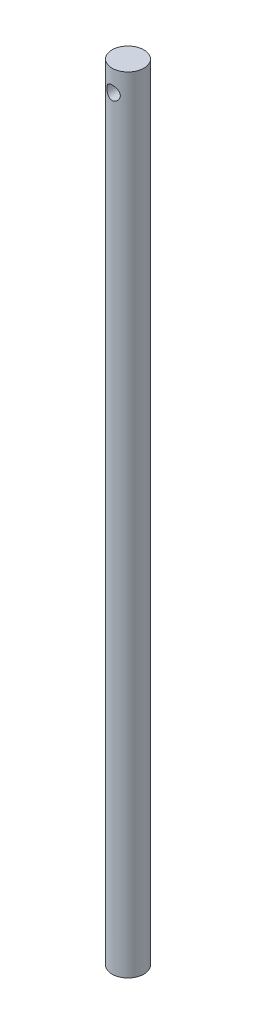
SolidWorks part; units mm, degrees
ref_plane "Frontal Plane" through (0, 0, 0) normal (0, 0, 1) x (1, 0, 0)
ref_plane "Horizontal Plane" through (0, 0, 0) normal (0, 1, 0) x (1, 0, 0)
ref_plane "Profile Plane" through (0, 0, 0) normal (1, 0, 0) x (0, 0, -1)
sketch "Sketch1" plane through (0, 0, 0) normal (0, 1, 0) x (1, 0, 0)
  circle A0 centre (0, 0) radius 7.5
  dimension "D1" = 15
extrude "Boss-Extrude1" add sketch "Sketch1" along normal blind 350
ref_plane "Plane1" through (0, 350, 0) normal (0, 1, 0) x (1, 0, 0)
sketch "Sketch3" plane through (0, 350, 0) normal (0, 1, 0) x (1, 0, 0)
  circle A0 centre (0, 0) radius 7.5
  circle A1 centre (0, 0) radius 7.5 construction
extrude "Boss-Extrude2" add sketch "Sketch3" along normal blind 20
sketch "Sketch4" plane through (0, 0, 0) normal (0, 0, 1) x (1, 0, 0)
  line L0 (7.5, 370) -> (-7.5, 370) construction
  circle A0 centre (0, 360) radius 3.175
  dimension "D2" = 6.35
  dimension "D1" = 10
extrude "Cut-Extrude1" cut sketch "Sketch4" against normal through all both and the other way through all
equation "\"WallThickness\"= 0.5cm"
equation "\"Box-X\"= 40cm"
equation "\"Box-Z\"= 20cm"
equation "\"Box-Y\"= 30cm"
equation "\"BottomPlateX\"= 100cm"
equation "\"ArmPlateX\"= 50cm"
equation "\"ArmPlateThickness\"= 1cm"
equation "\"DCMotor1D\"= 65mm"
equation "\"DCMotor1L\"= 215mm"
equation "\"DCMotor1ShaftL\"= 30mm"
equation "\"DCMotor2X\"= 68mm"
equation "\"DCMotor2D\"= 65mm"
equation "\"DCMotor2L\"= 208mm"
equation "\"DCMotor2ShaftL\"= 39mm"
equation "\"BenchDepth\"= 5cm"
equation "\"BenchH\"= 10cm"
equation "\"BenchL\"= 15cm"
equation "\"ActuatorPinD\"= 6.35mm"
equation "\"D2\"= \"ActuatorPinD\""
equation "\"D2@Sketch4\"=\"ActuatorPinD\""
equation "\"D1@Boss-Extrude1\"=\"ActuatorL\""
